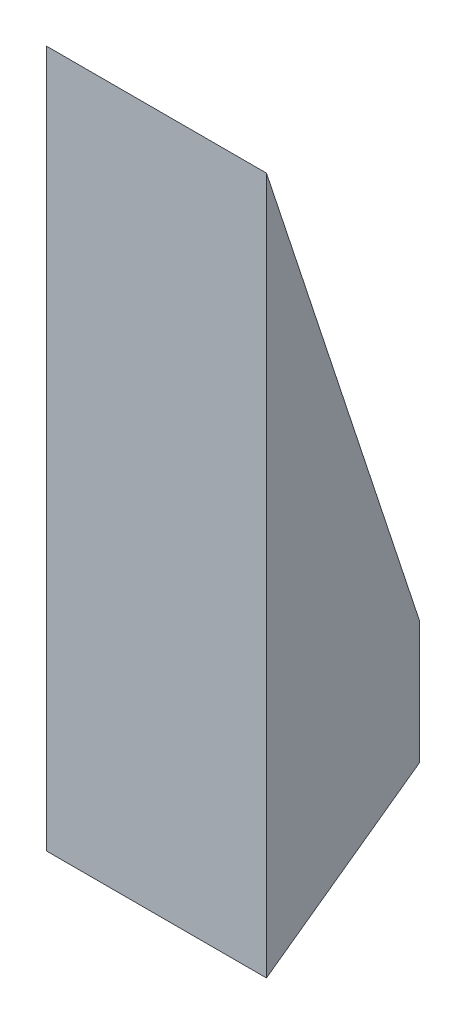
SolidWorks part; units mm, degrees
ref_plane "Alzado" through (0, 0, 0) normal (0, 0, 1) x (1, 0, 0)
ref_plane "Planta" through (0, 0, 0) normal (0, 1, 0) x (1, 0, 0)
ref_plane "Vista lateral" through (0, 0, 0) normal (1, 0, 0) x (0, 0, -1)
sketch "Croquis1" plane through (0, 0, 0) normal (0, 1, 0) x (1, 0, 0)
  line L0 (27, 0) -> (-27, 0)
  line L1 (-27, 0) -> (0, 64.5833)
  line L2 (27, 0) -> (0, 64.5833)
  point P4 (0, 0)
  dimension "D1" = 54
  dimension "D2" = 70
extrude "Saliente-Extruir1" add sketch "Croquis1" along normal blind 172
shell "Vaciado2" thickness 2
sketch "Croquis5" plane through (0, 0, 0) normal (1, 0, 0) x (0, 0, -1)
  line L0 (4.5228, 172) -> (64.5833, 172)
  line L1 (0, 172) -> (64.5833, 172) construction
  line L2 (64.5833, 172) -> (64.5833, 0)
  line L3 (64.5833, 172) -> (64.5833, 0) construction
  line L4 (64.5833, 0) -> (4.5228, 172)
  point P5 (64.6872, 20.9523)
  point P9 (64.6872, 0)
sketch "Croquis6" plane through (0, 0, 0) normal (0, -1, 0) x (1, 0, 0)
  line L0 (-27, 0) -> (27, 0)
  line L1 (27, 0) -> (0, -64.5833)
  line L2 (0, -64.5833) -> (-27, 0)
extrude "Saliente-Extruir2" add sketch "Croquis6" along normal blind 30
sketch "Croquis7" plane through (0, 0, 0) normal (1, 0, 0) x (0, 0, -1)
extrude "Cortar-Extruir2" cut sketch "Croquis5" against normal through all both and the other way through all
sketch "Croquis8" plane through (0, 2, 0) normal (0, 1, 0) x (1, 0, 0)
  line L0 (0, 59.3981) -> (0, 0) construction
  circle A0 centre (0, 48.788) radius 3.75
  circle A1 centre (0, 38.788) radius 3.75
  circle A2 centre (0, 28.788) radius 3.75
  circle A3 centre (0, 18.788) radius 3.75
  circle A4 centre (0, 8.788) radius 3.75
  circle A5 centre (10, 8.788) radius 3.75
  circle A6 centre (-10, 8.788) radius 3.75
  circle A7 centre (10, 18.788) radius 3.75
  circle A8 centre (-10, 18.788) radius 3.75
  circle A9 centre (8, 28.788) radius 3.75
  circle A10 centre (-8, 28.788) radius 3.75
  point P7 (0, 0)
  dimension "D1" = 7.5
  dimension "D2" = 5
  dimension "D3" = 2
  dimension "D4" = 2
  dimension "D5" = 2
  dimension "D6" = 2
  dimension "D7" = 2
  dimension "D8" = 2
extrude "Cortar-Extruir3" cut sketch "Croquis8" against normal blind 25 and the other way through all contours A3 | A9 | A2 | A1 | A0 | A10 | A8 | A7 | A4 | A6 | A5
sketch "Croquis9" plane through (0, 0, 0) normal (1, 0, 0) x (0, 0, -1)
  line L1 (0, 172) -> (61.6458, 172)
  line L2 (0, 172) -> (0, 141)
  line L3 (0, 141) -> (61.6458, 141)
  line L4 (61.6458, 172) -> (61.6458, 141)
  dimension "D1" = 31
extrude "Cortar-Extruir4" cut sketch "Croquis9" against normal through all both and the other way through all
sketch "Croquis10" plane through (0, 0, 0) normal (1, 0, 0) x (0, 0, -1)
  line L0 (0, 141) -> (64.5833, 0)
  line L1 (64.5833, 0) -> (23.7324, 141)
  line L2 (23.7324, 141) -> (0, 141)
extrude "Cortar-Extruir5" cut sketch "Croquis10" against normal through all both and the other way through all
